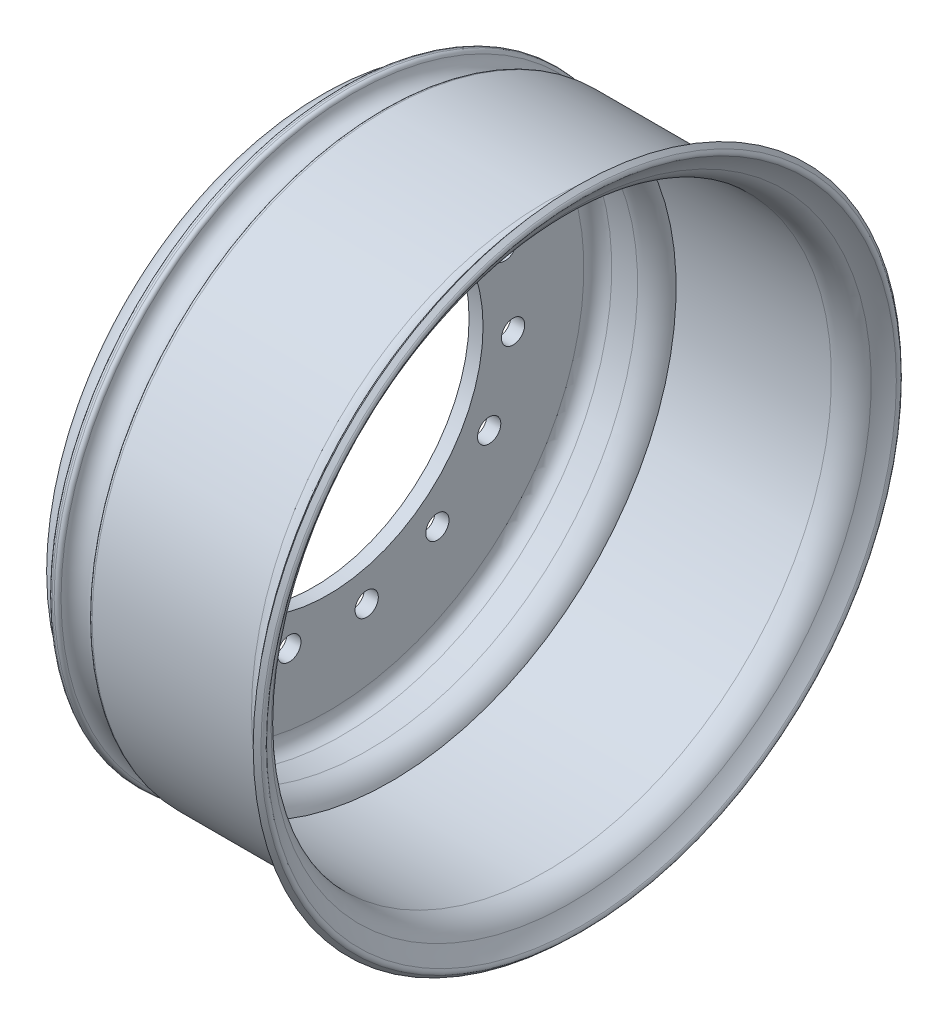
SolidWorks part; units mm, degrees
ref_plane "Front Plane" through (0, 0, 0) normal (0, 0, 1) x (1, 0, 0)
ref_plane "Top Plane" through (0, 0, 0) normal (0, 1, 0) x (1, 0, 0)
ref_plane "Right Plane" through (0, 0, 0) normal (1, 0, 0) x (0, 0, -1)
sketch "Sketch1" plane through (0, 0, 0) normal (0, 0, 1) x (1, 0, 0)
  line L0 (0, 0) -> (45.8987, 0) construction
  line L1 (6, 190) -> (0, 190)
  line L2 (26, 190) -> (131, 190)
  line L3 (1.1676, 184) -> (0, 184)
  line L4 (30.8324, 184) -> (131, 184)
  line L5 (0, 190) -> (0, 184)
  line L6 (1.6125, 183) -> (-0.6541, 183)
  line L7 (16, 174) -> (-0.6541, 174)
  line L8 (-9.6541, 165) -> (-9.6541, 100)
  line L9 (-18.6541, 165) -> (-18.6541, 100)
  line L10 (-18.6541, 100) -> (-9.6541, 100)
  line L11 (151, 208.9038) -> (155.3992, 204.8238)
  arc A0 (26, 190) -> (6, 190) centre (16, 190) cw
  arc A1 (131, 190) -> (141.9127, 196.4038) centre (131, 202.5) ccw
  arc A2 (151, 208.9038) -> (141.9127, 196.4038) centre (198.6585, 164.7035) ccw
  arc A3 (30.8324, 184) -> (16, 174) centre (16, 190) cw
  arc A4 (131, 184) -> (147.1507, 193.4776) centre (131, 202.5) ccw
  arc A5 (155.3992, 204.8238) -> (147.1507, 193.4776) centre (198.6585, 164.7035) ccw
  arc A6 (-0.6541, 174) -> (-9.6541, 165) centre (-0.6541, 165) ccw
  arc A7 (-0.6541, 183) -> (-18.6541, 165) centre (-0.6541, 165) ccw
  arc A8 (1.6125, 183) -> (1.1676, 184) centre (16, 190) cw
  arc A9 (30.8324, 184) -> (1.1676, 184) centre (16, 190) cw construction
  dimension "D1" = 10
  dimension "D4" = 12.5
  dimension "D5" = 65
  dimension "D10" = 9
  dimension "D11" = 18
  dimension "D2" = 6
  dimension "D3" = 105
  dimension "D6" = 12.5
  dimension "D7" = 145
  dimension "D8" = 190
  dimension "D12" = 9
  dimension "D13" = 9
  dimension "D14" = 65
  dimension "D9" = 6
revolve "Revolve1" add sketch "Sketch1" angle 360 about L0
sketch "Sketch2" plane through (-18.6541, 0, 0) normal (-1, 0, 0) x (0, 0, 1)
  circle A0 centre (0, 120) radius 7.5
  point P2 (0, 0)
  dimension "D1" = 15
  dimension "D2" = 120
extrude "Cut-Extrude1" cut sketch "Sketch2" against normal through all
pattern_circular "CirPattern1" count 15 over 360 about axis through (0, 0, 0) along (1, 0, 0) of "Cut-Extrude1"
fillet "Fillet1" radius 2.5 1 edges at (155.3992, 0, 204.8238)
fillet "Fillet2" radius 2.5 2 edges at (26, 0, 190) (6, 0, 190)
fillet "Fillet3" radius 2.5 1 edges at (0, 0, 190)
